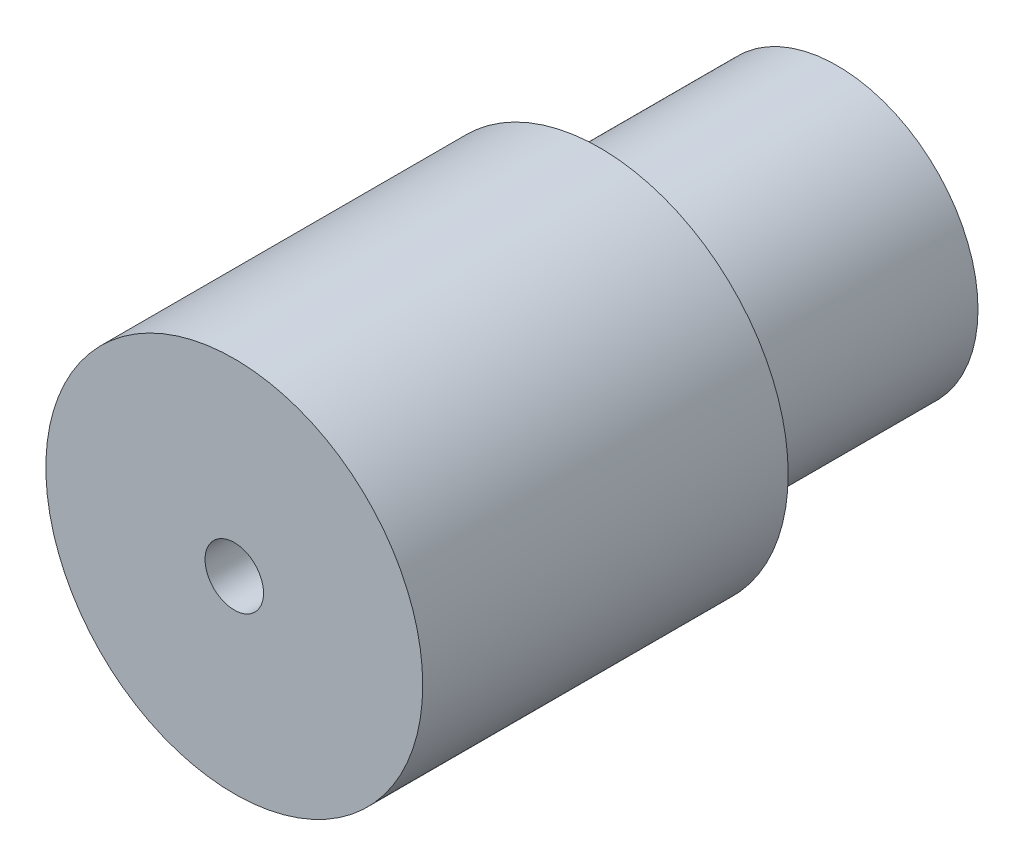
SolidWorks part; units mm, degrees
ref_plane "Piano frontale" through (0, 0, 0) normal (0, 0, 1) x (1, 0, 0)
ref_plane "Piano superiore" through (0, 0, 0) normal (0, 1, 0) x (1, 0, 0)
ref_plane "Piano destro" through (0, 0, 0) normal (1, 0, 0) x (0, 0, -1)
other "Graphic1"
other "Graphic (Closed) -1"
sketch "Sketch2" plane through (0, 0, 0) normal (0, 0, 1) x (1, 0, 0)
  circle A0 centre (0, 0) radius 5.1563
extrude "Boss-Extrude1" add sketch "Sketch2" against normal blind 10 contours A0
sketch "Sketch3" plane through (0, 0, -10) normal (0, 0, -1) x (-1, 0, 0)
  circle A0 centre (0, 0) radius 3.85
  dimension "D1" = 7.7
extrude "Boss-Extrude2" add sketch "Sketch3" along normal blind 6.5
sketch "Sketch5" plane through (0, 0, 0) normal (0, 0, 1) x (1, 0, 0)
  circle A0 centre (0, 0) radius 0.8
  dimension "D1" = 1.6
extrude "Cut-Extrude1" cut sketch "Sketch5" against normal through all and the other way through all contours A0
sketch "Sketch6" plane through (0, 0, 0) normal (0, 0, 1) x (1, 0, 0)
  circle A0 centre (0, 0) radius 7.5
  dimension "D1" = 15
